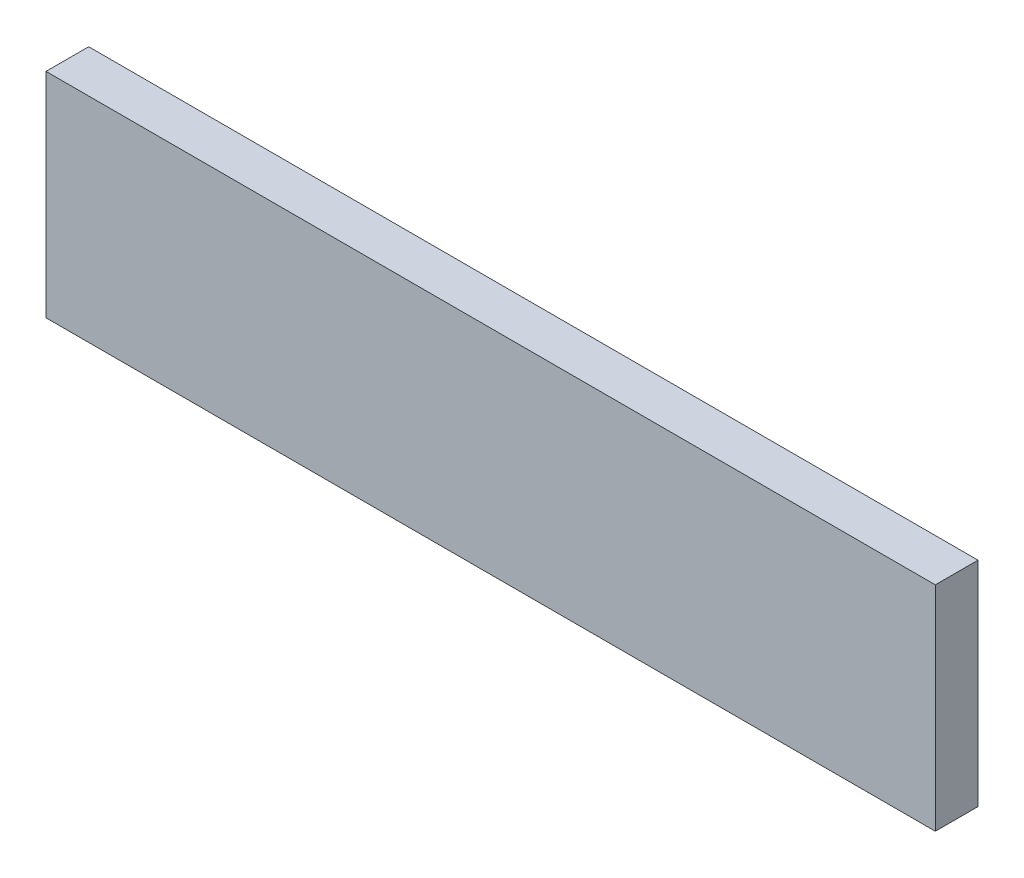
SolidWorks part; units mm, degrees
ref_plane "Alzado" through (0, 0, 0) normal (0, 0, 1) x (1, 0, 0)
ref_plane "Planta" through (0, 0, 0) normal (0, 1, 0) x (1, 0, 0)
ref_plane "Vista lateral" through (0, 0, 0) normal (1, 0, 0) x (0, 0, -1)
sketch "Croquis1" plane through (0, 0, 0) normal (0, 0, 1) x (1, 0, 0)
  line L1 (-41.7553, 12.8546) -> (-16.7553, 12.8546)
  line L2 (-41.7553, 12.8546) -> (-41.7553, 6.8546)
  line L3 (-41.7553, 6.8546) -> (-16.7553, 6.8546)
  line L4 (-16.7553, 12.8546) -> (-16.7553, 6.8546)
  dimension "D1" = 25
  dimension "D2" = 6
extrude "Saliente-Extruir1" add sketch "Croquis1" along normal blind 1.2
